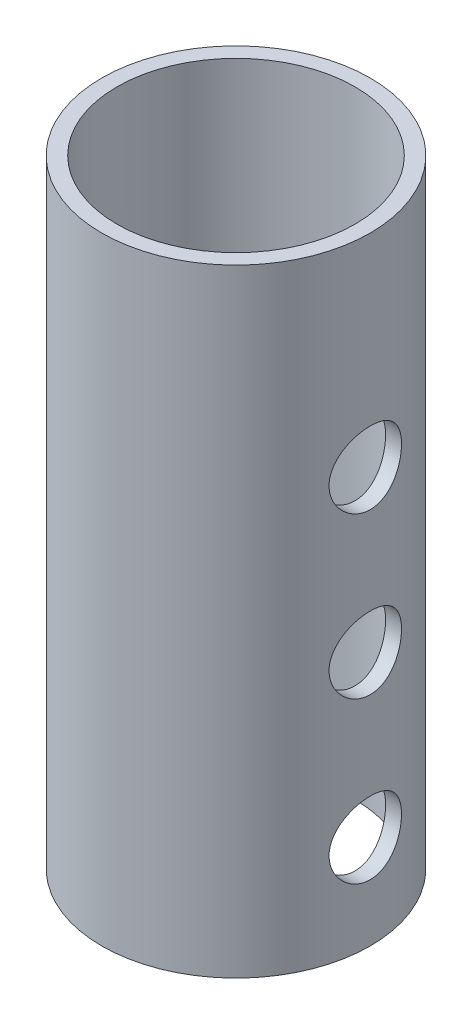
SolidWorks part; units mm, degrees
material "PTFE (general)"
ref_plane "Front Plane" through (0, 0, 0) normal (0, 0, 1) x (1, 0, 0)
ref_plane "Top Plane" through (0, 0, 0) normal (0, 1, 0) x (1, 0, 0)
ref_plane "Right Plane" through (0, 0, 0) normal (1, 0, 0) x (0, 0, -1)
sketch "Sketch1" plane through (0, 0, 0) normal (0, 1, 0) x (1, 0, 0)
  circle A0 centre (0, 0) radius 42.725
  circle A1 centre (0, 0) radius 37.875
  dimension "D1" = 85.45
  dimension "D2" = 75.75
extrude "Boss-Extrude1" add sketch "Sketch1" along normal blind 196.5
sketch "Sketch2" plane through (0, 0, 0) normal (1, 0, 0) x (0, 0, -1)
  line L0 (37.875, 196.5) -> (-37.875, 196.5) construction
  circle A0 centre (0, 131.8) radius 11.53
  circle A1 centre (0, 80.8) radius 11.53
  circle A2 centre (0, 29.8) radius 11.53
  dimension "D2" = 23.06
  dimension "D3" = 23.06
  dimension "D4" = 23.06
  dimension "D1" = 64.7
  dimension "D5" = 51
  dimension "D6" = 51
extrude "Cut-Extrude1" cut sketch "Sketch2" along normal through all
sketch "Sketch4" plane through (0, 0, 0) normal (1, 0, 0) x (0, 0, -1)
  circle A0 centre (0, 106.3) radius 7.5
  circle A4 centre (0, 80.8) radius 11.53 construction
  dimension "D1" = 15
  dimension "D3" = 25.5
extrude "Cut-Extrude2" cut sketch "Sketch4" against normal through all
